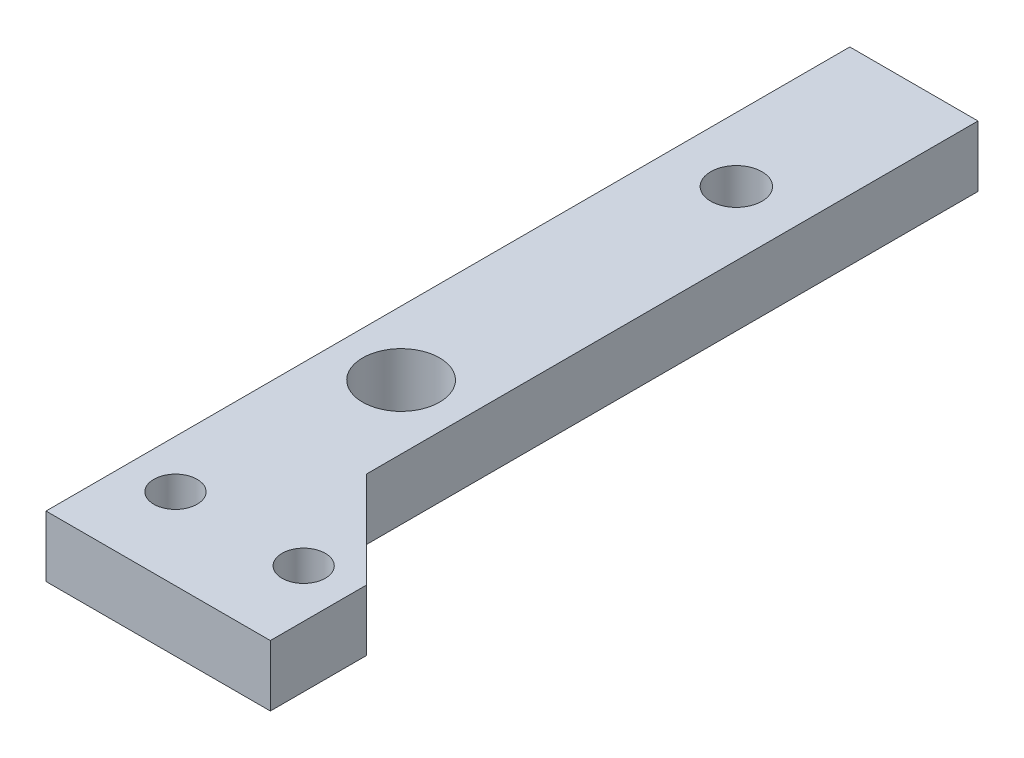
SolidWorks part; units mm, degrees
ref_plane "Front Plane" through (0, 0, 0) normal (0, 0, 1) x (1, 0, 0)
ref_plane "Top Plane" through (0, 0, 0) normal (0, 1, 0) x (1, 0, 0)
ref_plane "Right Plane" through (0, 0, 0) normal (1, 0, 0) x (0, 0, -1)
sketch "Sketch2" plane through (0, 0, 0) normal (0, 1, 0) x (1, 0, 0)
  line L0 (10, 0) -> (10, -100) construction
  line L1 (0, 0) -> (20, 0)
  line L2 (0, 0) -> (0, -100)
  line L3 (0, -100) -> (20, -100)
  line L4 (20, 0) -> (20, -100)
  circle A0 centre (10, -80) radius 6
  circle A1 centre (10, -27.7) radius 4
  dimension "D3" = 8
  dimension "D4" = 12
  dimension "D1" = 100
  dimension "D2" = 20
  dimension "D5" = 52.3
  dimension "D6" = 20
extrude "Boss-Extrude1" add sketch "Sketch2" along normal blind 9.525
sketch "Sketch4" plane through (0, 9.525, 0) normal (0, 1, 0) x (1, 0, 0)
  line L0 (0, -100) -> (20, -100) construction
  line L1 (0, -100) -> (20, -100)
  line L2 (0, -100) -> (0, -125.4)
  line L3 (0, -125.4) -> (20, -125.4)
  line L4 (20, -100) -> (20, -125.4)
  point P4 (16.7968, -100)
  dimension "D1" = 25.4
extrude "Boss-Extrude2" add sketch "Sketch4" against normal up to surface (9.525 mm away) up to face at (10, 0, 50)
sketch "Sketch8" plane through (0, 9.525, 0) normal (0, 1, 0) x (1, 0, 0)
  line L0 (20, -125.4) -> (35, -125.4)
  line L1 (35, -125.4) -> (35, -110.4)
  line L2 (35, -110.4) -> (20, -95.4)
  line L3 (20, -125.4) -> (20, 0) construction
  line L4 (20, -95.4) -> (20, -125.4)
  point P3 (30.8359, -103.8677)
  dimension "D1" = 45
  dimension "D2" = 15
  dimension "D3" = 15
extrude "Boss-Extrude3" add sketch "Sketch8" against normal up to surface (9.525 mm away) up to face at (10, 0, 62.7)
sketch "Sketch5" plane through (0, 9.525, 0) normal (0, 1, 0) x (1, 0, 0)
  line L0 (17.5, -125.4) -> (17.5, -112.7) construction
  line L1 (0, -125.4) -> (35, -125.4) construction
  line L2 (7.5, -112.7) -> (27.5, -112.7) construction
  point P4 (0, 0)
  point P7 (17.5, -112.7)
  point P8 (0, 0)
  dimension "D1" = 12.7
  dimension "D2" = 20
hole_wizard "1/4 Clearance Hole2" positions "Sketch9" profile "Sketch10" hole size "1/4" standard "ANSI Inch" end condition through all
sketch "Sketch9" plane through (0, 9.525, 0) normal (0, 1, 0) x (1, 0, 0)
  point P0 (7.5, -112.7)
  point P3 (27.5, -112.7)
sketch "Sketch10" plane through (7.5, 9.525, 112.7) normal (1, 0, 0) x (0, 0, 1)
  line L0 (0, 0) -> (0, 9.525)
  line L1 (0, 9.525) -> (3.3782, 9.525)
  line L2 (3.3782, 9.525) -> (3.3782, 0)
  line L5 (3.3782, 0) -> (0, 0)
  line L11 (0, -6.35) -> (0, 107.95) construction
  dimension "Thru Hole Dia." = 6.7564
  dimension "Thru Hole Depth" = 9.525
